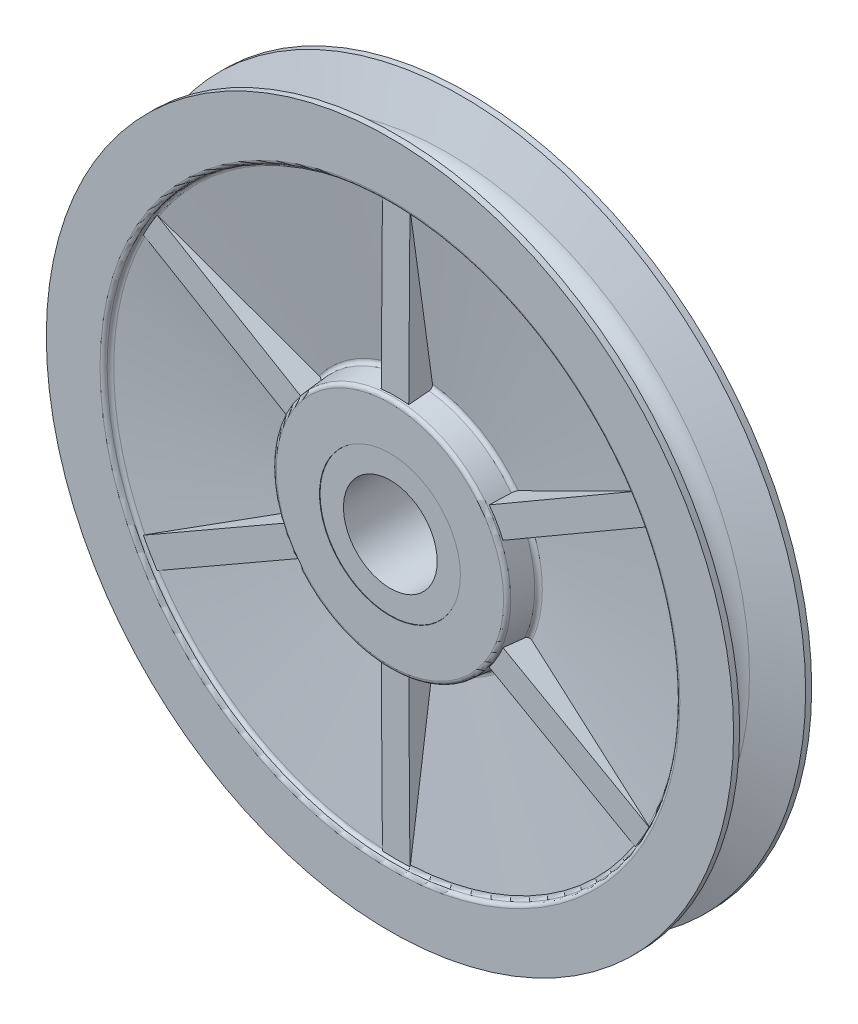
SolidWorks part; units mm, degrees
ref_plane "Front" through (0, 0, 0) normal (0, 0, 1) x (1, 0, 0)
ref_plane "Top" through (0, 0, 0) normal (0, 1, 0) x (1, 0, 0)
ref_plane "Right" through (0, 0, 0) normal (1, 0, 0) x (0, 0, -1)
sketch "Sketch1" plane through (0, 0, 0) normal (1, 0, 0) x (0, 0, -1)
  line L0 (6.7056, 69.85) -> (7.9375, 69.85)
  line L1 (-6.7056, 69.85) -> (-7.9375, 69.85)
  line L2 (-6.7056, 69.85) -> (-3.7459, 61.395)
  line L3 (7.9375, 23.8125) -> (7.9375, 14.2875)
  line L4 (7.8613, 9.525) -> (-7.8613, 9.525)
  line L5 (-7.9375, 14.2875) -> (-7.9375, 23.8125)
  line L6 (6.7056, 69.85) -> (3.7459, 61.395)
  line L8 (-7.9375, 0) -> (7.9375, 0) construction
  line L10 (7.9375, 69.85) -> (7.9375, 58.2295)
  line L12 (-7.9375, 14.2875) -> (-7.8613, 14.2875)
  line L13 (-7.8613, 14.2875) -> (-7.8613, 9.525)
  line L14 (0, 58.7375) -> (0, -58.7375) construction
  line L15 (7.8613, 14.2875) -> (7.9375, 14.2875)
  line L16 (7.8613, 14.2875) -> (7.8613, 9.525)
  line L17 (-7.9375, 69.85) -> (-7.9375, -69.85) construction
  line L18 (-7.9375, 58.2295) -> (-6.6675, 58.2295)
  line L19 (-6.6675, 58.2295) -> (-1.905, 23.8125)
  line L20 (-1.905, 23.8125) -> (-7.9375, 23.8125)
  line L21 (-7.9375, 58.2295) -> (-7.9375, 69.85)
  line L22 (7.9375, 58.2295) -> (6.6675, 58.2295)
  line L23 (6.6675, 58.2295) -> (1.905, 23.8125)
  line L24 (1.905, 23.8125) -> (7.9375, 23.8125)
  arc A0 (-3.7459, 61.395) -> (3.7459, 61.395) centre (0, 62.7062) ccw
  circle A1 centre (0, 62.7062) radius 3.9687 construction
  circle A2 centre (0, 0) radius 9.525 construction
  circle A3 centre (0, 0) radius 14.2875 construction
  circle A4 centre (0, 0) radius 23.8125 construction
  circle A5 centre (0, -62.7062) radius 3.9688 construction
  point P28 (-7.9375, 0)
  dimension "Rope Dia" = 7.9375
  dimension "Shaft Dia" = 19.05
  dimension "D1" = 28.575
  dimension "D3" = 47.625
  dimension "Wd" = 15.875
  dimension "D8" = 1.2319
  dimension "D9" = 0.0762
  dimension "Groove Dia" = 117.475
  dimension "OD" = 139.7
  dimension "D4" = 0.508
  dimension "D2" = 1.27
  dimension "D5" = 3.81
revolve "Revolve1" add sketch "Sketch1" angle 360 about L8
sketch "Sketch2" plane through (0, 0, 0) normal (0, 0, 1) x (1, 0, 0)
  circle A0 centre (0, 0) radius 14.2875 construction
  circle A1 centre (0, 0) radius 14.2875
extrude "Cut-Extrude-Thin1" cut sketch "Sketch2" against normal through all and the other way through all thin
draft "Draft1" type of draft neutral plane draft angle 5 faces to draft 2 face at (23.8125, 0, 7.9375) face at (58.2295, 0, 6.6675) neutral plane through (0, 58.2295, 7.9375) neutral plane normal (0, 0, 1) parameters "D1"=5
draft "Draft2" type of draft neutral plane draft angle 15 faces to draft 2 face at (23.8125, 0, -1.905) face at (58.2295, 0, -7.9375) neutral plane through (0, 69.85, -7.9375) neutral plane normal (0, 0, -1) parameters "D1"=15
fillet "Fillet1" radius 0.762 4 edges at (58.2295, 0, 7.9375) (58.2295, 0, -7.9375) (23.8125, 0, 7.9375) (23.8125, 0, -7.9375)
fillet "Fillet2" radius 0.762 2 edges at (-24.334, 0, 1.9772) (58.117, 0, 6.6519)
sketch "Sketch5" plane through (0, 0, 0) normal (1, 0, 0) x (0, 0, -1)
  line L0 (-6.9215, 22.5425) -> (-6.6675, 58.2295)
  line L1 (0, 58.7375) -> (0, -58.7375) construction
  line L6 (-6.6675, 58.2295) -> (0, 58.2295)
  line L7 (0, 58.2295) -> (0, 14.2875)
  line L11 (-6.9215, 22.5425) -> (-6.9215, 14.2875)
  line L12 (-6.9215, 14.2875) -> (0, 14.2875)
  line L13 (-1.905, 23.8125) -> (-7.9375, 23.8125) construction
  line L14 (-7.9375, 14.2875) -> (-7.9375, 23.8125) construction
  dimension "D1" = 1.27
  dimension "D2" = 1.016
extrude "Boss-Extrude1" add sketch "Sketch5" along normal mid plane 5.588
mirror "Mirror1" about plane through (0, 0, 0) normal (0, 0, 1) of "Boss-Extrude1"
pattern_circular "CirPattern1" count 6 over 360 about axis through (0, 0, 0) along (0, 0, 1) of "Mirror1", "Boss-Extrude1"
equation "\"D1@Sketch1\" = \"Shaft Dia@Sketch1\" * 1.5"
equation "\"D3@Sketch1\" = \"Shaft Dia@Sketch1\" * 2.5"
equation "\"D1@Boss-Extrude1\" = \"OD@Sketch1\" * .04"
